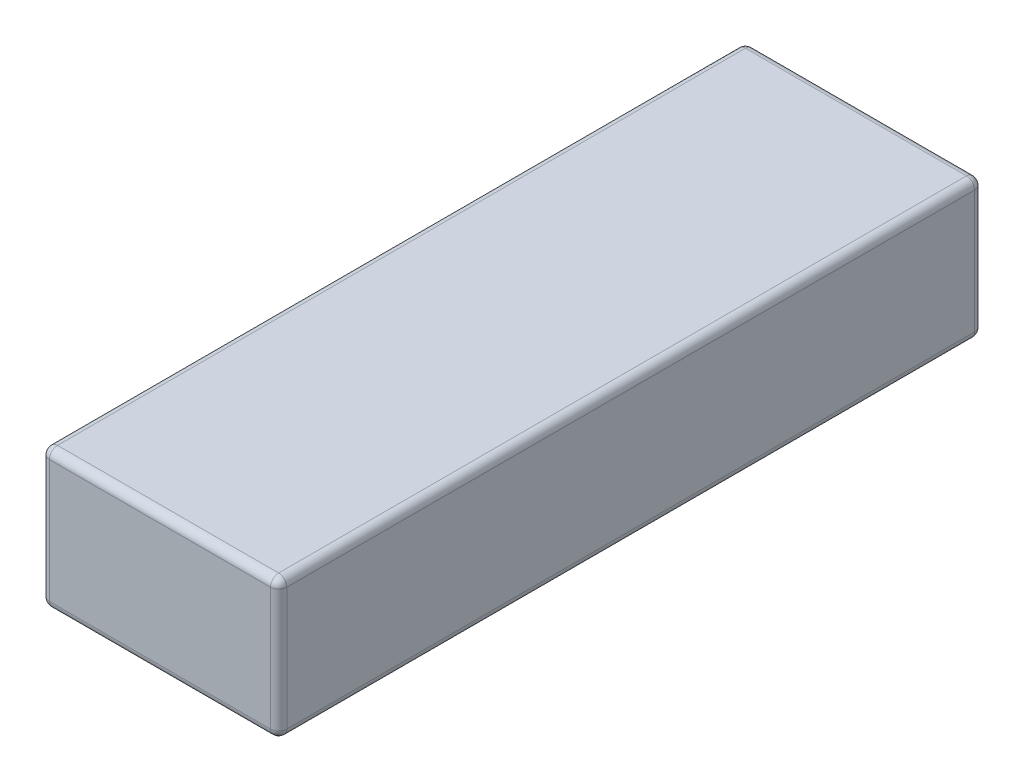
SolidWorks part; units mm, degrees
other "Markup1"
sketch "Sketch2" plane through (-14.5, 8.5, 0) normal (-0.3581, 0.381, -0.8524) x (-0.7829, 0.3749, 0.4965)
material "ABS PC"
ref_plane "Front Plane" through (0, 0, 0) normal (0, 0, 1) x (1, 0, 0)
ref_plane "Top Plane" through (0, 0, 0) normal (0, 1, 0) x (1, 0, 0)
ref_plane "Right Plane" through (0, 0, 0) normal (1, 0, 0) x (0, 0, -1)
sketch "Sketch1" plane through (0, 0, 0) normal (0, 0, 1) x (1, 0, 0)
  line L1 (-14.5, -8.5) -> (14.5, -8.5)
  line L2 (-14.5, -8.5) -> (-14.5, 8.5)
  line L3 (-14.5, 8.5) -> (14.5, 8.5)
  line L4 (14.5, -8.5) -> (14.5, 8.5)
  line L5 (0, 8.5) -> (0, -8.5) construction
  line L6 (-14.5, 0) -> (14.5, 0) construction
  point P0 (0, 0)
  dimension "D1" = 17
  dimension "D2" = 29
extrude "Boss-Extrude1" add sketch "Sketch1" along normal blind 86
fillet "Fillet1" radius 1 12 edges at (-14.5, -8.5, 43) (14.5, -8.5, 43) (14.5, 8.5, 43) (0, -8.5, 86) (-14.5, 0, 86) (0, 8.5, 86) (14.5, 0, 86) (0, 8.5, 0) (-14.5, 0, 0) (0, -8.5, 0) (14.5, 0, 0) (-14.5, 8.5, 43)
